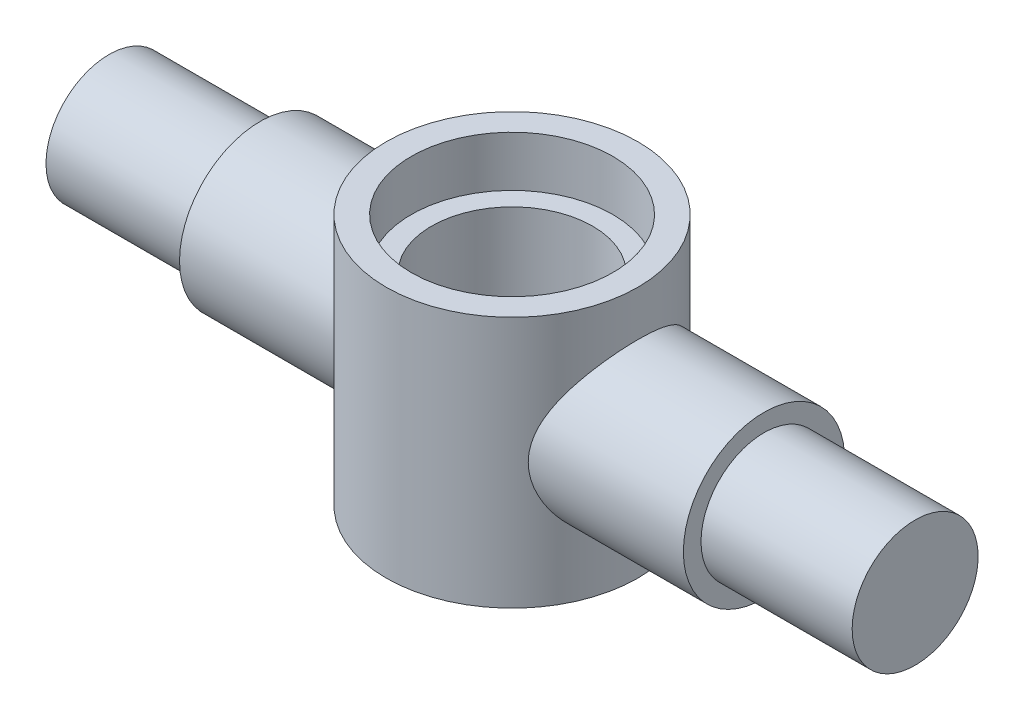
SolidWorks part; units mm, degrees
ref_plane "Front Plane" through (0, 0, 0) normal (0, 0, 1) x (1, 0, 0)
ref_plane "Top Plane" through (0, 0, 0) normal (0, 1, 0) x (1, 0, 0)
ref_plane "Right Plane" through (0, 0, 0) normal (1, 0, 0) x (0, 0, -1)
sketch "Sketch1" plane through (0, 0, 0) normal (0, 0, 1) x (1, 0, 0)
  line L0 (0, -25) -> (25, -25)
  line L1 (25, -25) -> (25, 25)
  line L2 (25, 25) -> (0, 25)
  line L3 (0, 25) -> (0, -25)
  dimension "D1" = 25
  dimension "D2" = 50
  dimension "D3" = 25
revolve "Revolve1" add sketch "Sketch1" angle 360 about L3
sketch "Sketch2" plane through (0, 0, 0) normal (0, 0, 1) x (1, 0, 0)
  line L0 (-80, 0) -> (80, 0)
  line L1 (80, 0) -> (80, 12.5)
  line L2 (80, 12.5) -> (50, 12.5)
  line L3 (50, 12.5) -> (50, 16)
  line L4 (50, 16) -> (-50, 16)
  line L5 (0, -27.5) -> (0, 27.5) construction
  line L6 (-50, 12.5) -> (-50, 16)
  line L7 (-80, 12.5) -> (-50, 12.5)
  line L8 (-80, 0) -> (-80, 12.5)
  point P10 (0, 16)
  point P13 (0, 0)
  dimension "D1" = 80
  dimension "D2" = 50
  dimension "D3" = 12.5
  dimension "D4" = 16
revolve "Revolve2" add sketch "Sketch2" angle 360 about L0
sketch "Sketch3" plane through (0, 0, 0) normal (0, 0, 1) x (1, 0, 0)
  line L0 (0, 25) -> (20, 25)
  line L1 (20, 25) -> (20, 15)
  line L2 (20, 15) -> (16, 15)
  line L3 (16, 15) -> (16, -25)
  line L4 (16, -25) -> (0, -25)
  line L5 (0, -25) -> (0, 25)
  line L6 (-25, -25) -> (25, -25) construction
  line L7 (25, 25) -> (-25, 25) construction
  dimension "D1" = 10
  dimension "D2" = 16
  dimension "D3" = 20
revolve "Cut-Revolve1" cut sketch "Sketch3" angle 360 about L5
